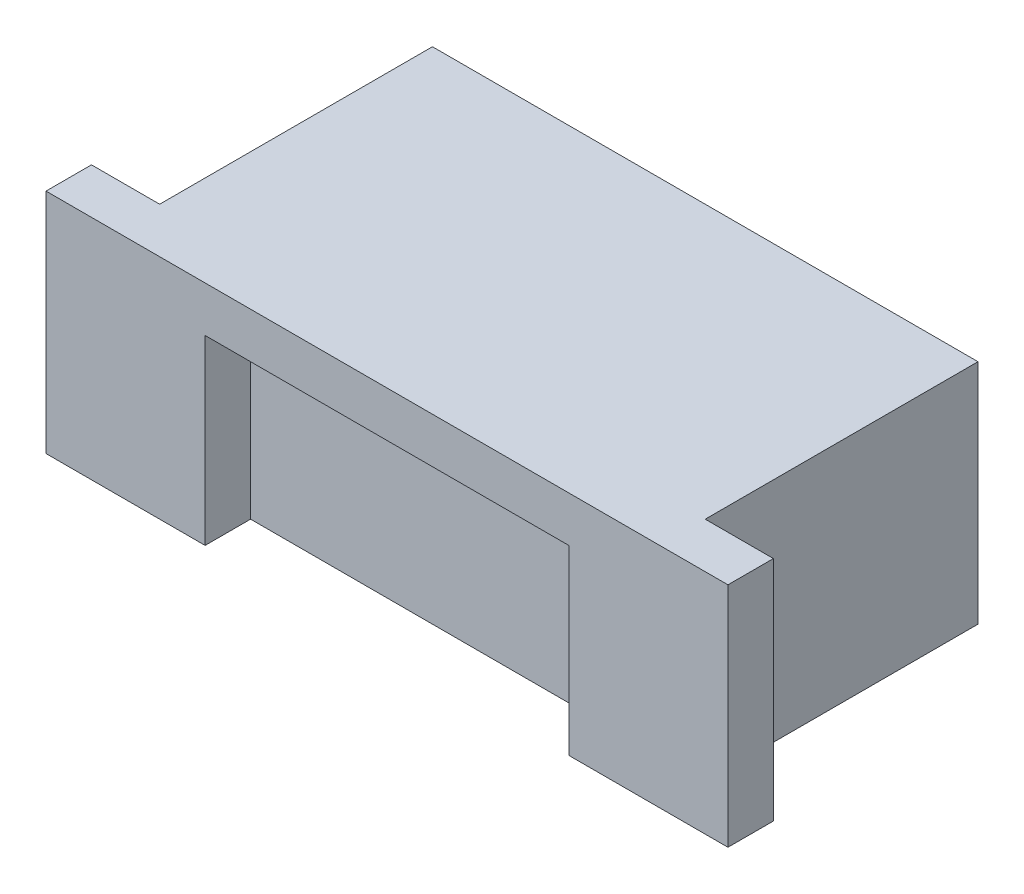
SolidWorks part; units mm, degrees
ref_plane "Płaszczyzna przednia" through (0, 0, 0) normal (0, 0, 1) x (1, 0, 0)
ref_plane "Płaszczyzna górna" through (0, 0, 0) normal (0, 1, 0) x (1, 0, 0)
ref_plane "Płaszczyzna prawa" through (0, 0, 0) normal (1, 0, 0) x (0, 0, -1)
sketch "Sketch1" plane through (0, 0, 0) normal (0, 1, 0) x (1, 0, 0)
  line L0 (0, 0) -> (7.5, 0)
  line L1 (7.5, 0) -> (7.5, 0.5)
  line L2 (7.5, 0.5) -> (6.75, 0.5)
  line L3 (6.75, 0.5) -> (6.75, 3.5)
  line L4 (6.75, 3.5) -> (0.75, 3.5)
  line L5 (0.75, 3.5) -> (0.75, 0.5)
  line L6 (0.75, 0.5) -> (0, 0.5)
  line L7 (0, 0.5) -> (0, 0)
  line L8 (3.75, 3.5) -> (3.75, 0) construction
  dimension "D1" = 0.5
  dimension "D2" = 7.5
  dimension "D3" = 6
  dimension "D4" = 3
extrude "Boss-Extrude1" add sketch "Sketch1" along normal blind 2.5
sketch "Sketch2" plane through (0, 0, 0) normal (0, 0, 1) x (1, 0, 0)
  line L0 (0, 0) -> (7.5, 0) construction
  line L1 (1.75, 0) -> (5.75, 0)
  line L2 (1.75, 0) -> (1.75, 2)
  line L3 (1.75, 2) -> (5.75, 2)
  line L4 (5.75, 0) -> (5.75, 2)
  line L5 (3.75, 2) -> (3.75, 0) construction
  dimension "D1" = 2
  dimension "D2" = 4
extrude "Cut-Extrude1" cut sketch "Sketch2" against normal blind 0.5
